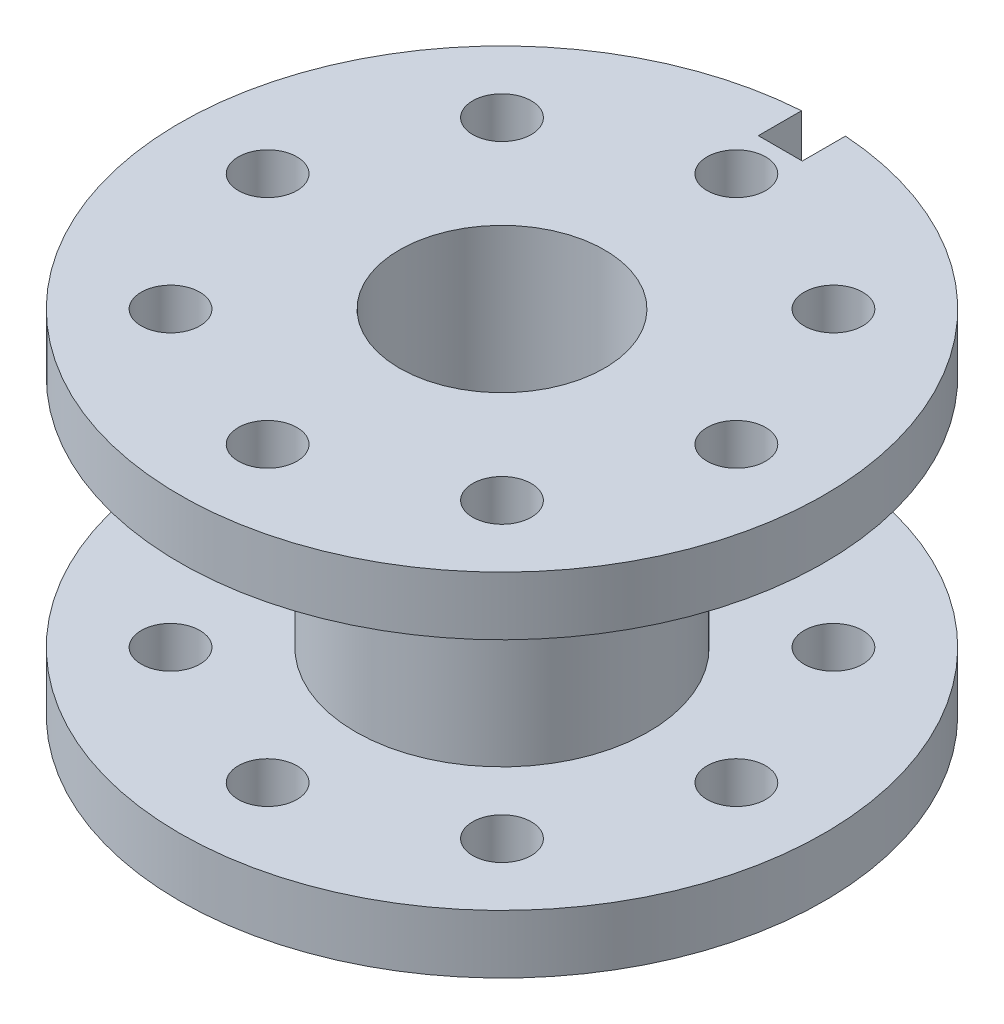
SolidWorks part; units mm, degrees
material "1060 Alloy"
ref_plane "Front Plane" through (0, 0, 0) normal (0, 0, 1) x (1, 0, 0)
ref_plane "Top Plane" through (0, 0, 0) normal (0, 1, 0) x (1, 0, 0)
ref_plane "Right Plane" through (0, 0, 0) normal (1, 0, 0) x (0, 0, -1)
sketch "Sketch1" plane through (0, 0, 0) normal (0, 1, 0) x (1, 0, 0)
  circle A0 centre (0, 0) radius 11
  circle A1 centre (0, 8) radius 1
  circle A2 centre (5.6569, 5.6569) radius 1
  circle A3 centre (8, 0) radius 1
  circle A4 centre (5.6569, -5.6569) radius 1
  circle A5 centre (0, -8) radius 1
  circle A6 centre (-5.6569, -5.6569) radius 1
  circle A7 centre (-8, 0) radius 1
  circle A8 centre (-5.6569, 5.6569) radius 1
  point P22 (0, 0)
  dimension "D1" = 22
  dimension "D2" = 2
  dimension "D6" = 8
  dimension "D3" = 8
  dimension "D5" = 8
  dimension "D4" = 8
extrude "Boss-Extrude1" add sketch "Sketch1" along normal blind 12
sketch "Sketch2" plane through (0, 12, 0) normal (0, 1, 0) x (1, 0, 0)
  circle A0 centre (0, 0) radius 3.5
  dimension "D1" = 7
extrude "Cut-Extrude1" cut sketch "Sketch2" against normal through all
ref_plane "Plane1" through (0, 10, 0) normal (0, 1, 0) x (1, 0, 0)
sketch "Sketch3" plane through (0, 10, 0) normal (0, 1, 0) x (1, 0, 0)
  circle A0 centre (0, 0) radius 5
  circle A1 centre (0, 0) radius 11
  dimension "D1" = 10
  dimension "D2" = 22
extrude "Cut-Extrude2" cut sketch "Sketch3" against normal blind 8
sketch "Sketch4" plane through (0, 12, 0) normal (0, 1, 0) x (1, 0, 0)
  line L1 (-0.75, 12.5) -> (0.75, 12.5)
  line L2 (-0.75, 12.5) -> (-0.75, 9.5)
  line L3 (-0.75, 9.5) -> (0.75, 9.5)
  line L4 (0.75, 12.5) -> (0.75, 9.5)
  line L5 (-0.75, 12.5) -> (0.75, 9.5) construction
  line L6 (-0.75, 9.5) -> (0.75, 12.5) construction
  circle A0 centre (0, 0) radius 11 construction
  point P0 (0, 11)
  dimension "D1" = 1.5
  dimension "D2" = 3
extrude "Cut-Extrude3" cut sketch "Sketch4" against normal blind 4
